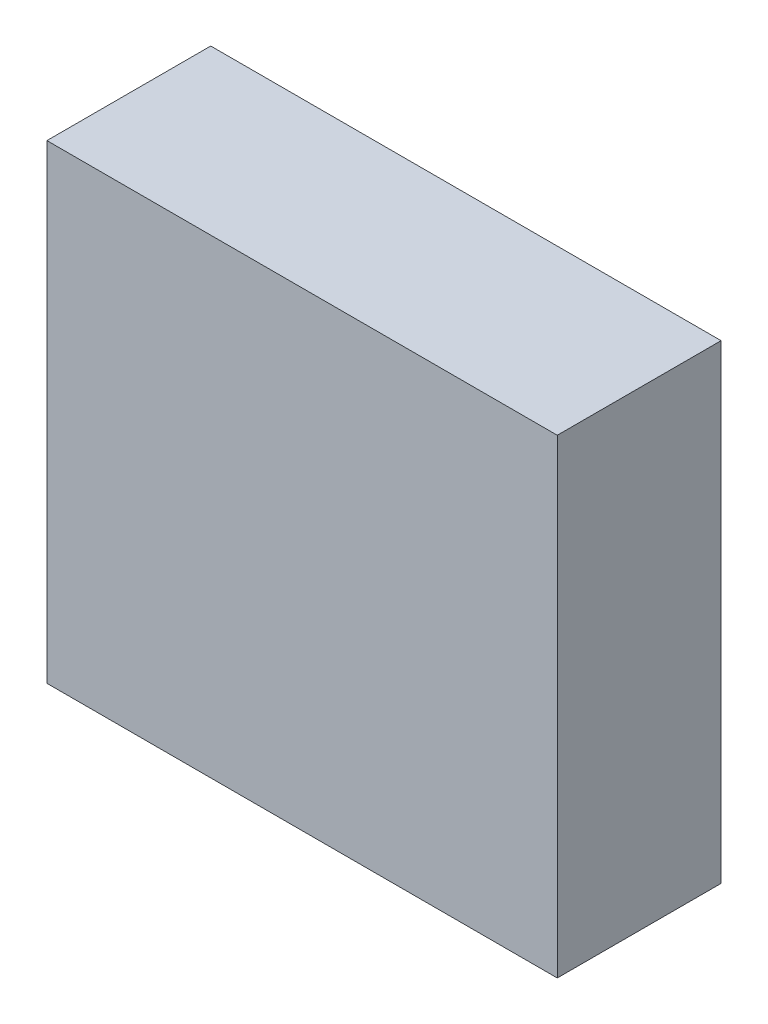
SolidWorks part; units mm, degrees
ref_plane "前视基准面" through (0, 0, 0) normal (0, 0, 1) x (1, 0, 0)
ref_plane "上视基准面" through (0, 0, 0) normal (0, 1, 0) x (1, 0, 0)
ref_plane "右视基准面" through (0, 0, 0) normal (1, 0, 0) x (0, 0, -1)
sketch "草图1" plane through (0, 0, 0) normal (0, 0, 1) x (1, 0, 0)
  line L0 (-5.125, -5.475) -> (5.125, -5.475)
  line L1 (5.125, -5.475) -> (5.125, 3.965)
  line L2 (5.125, 3.965) -> (-5.125, 3.965)
  line L3 (-5.125, 3.965) -> (-5.125, -5.475)
extrude "凸台-拉伸1" add sketch "草图1" along normal blind 3.29 from offset 0
